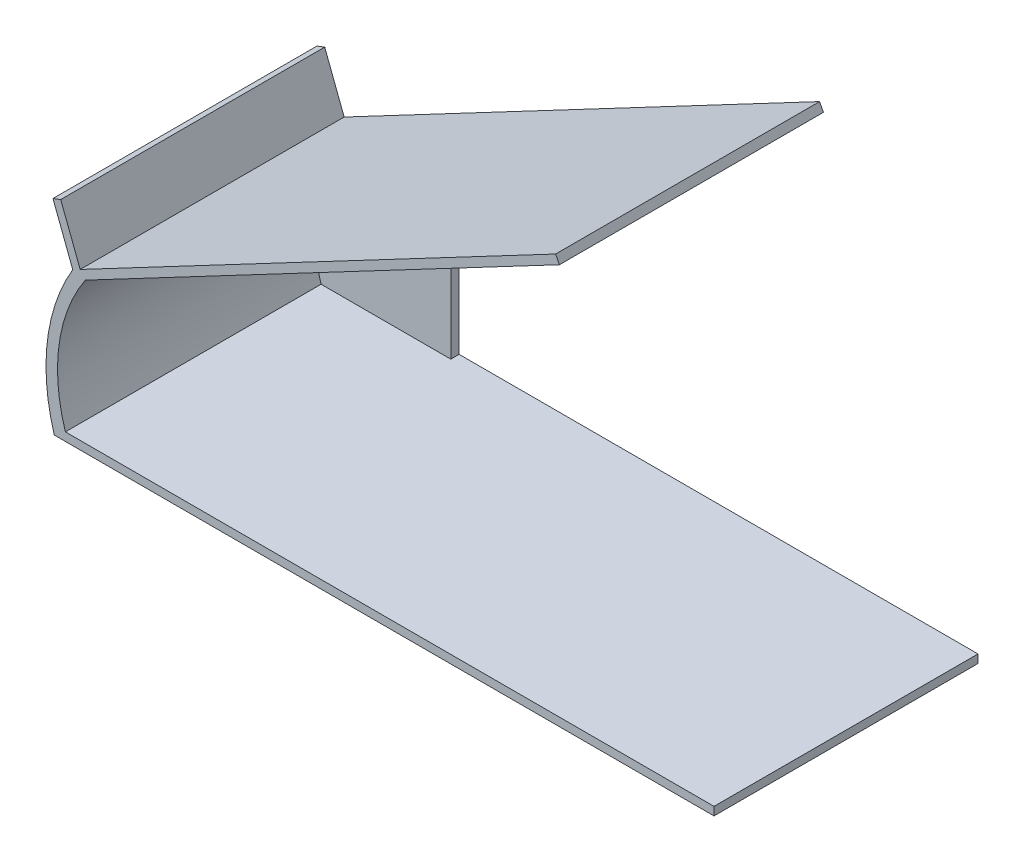
SolidWorks part; units mm, degrees
ref_plane "Front Plane" through (0, 0, 0) normal (0, 0, 1) x (1, 0, 0)
ref_plane "Top Plane" through (0, 0, 0) normal (0, 1, 0) x (1, 0, 0)
ref_plane "Right Plane" through (0, 0, 0) normal (1, 0, 0) x (0, 0, -1)
sketch "Sketch1" plane through (0, 0, 0) normal (0, 0, 1) x (1, 0, 0)
  line L0 (241, 0) -> (3, 0)
  line L1 (0, 0) -> (241, 0) construction
  line L2 (0, 0) -> (0, 147) construction
  line L3 (0, 147) -> (241, 147) construction
  line L4 (241, 0) -> (241, 147) construction
  line L5 (241, 0) -> (241, 3)
  line L6 (241, 3) -> (7, 3)
  line L7 (14.1823, 54) -> (185.251, 144.3472)
  line L8 (185.251, 144.3472) -> (183.85, 147)
  line L9 (183.85, 147) -> (9.6518, 55)
  arc A0 (9.6518, 55) -> (3, 0) centre (68.2435, 20.0115) ccw
  arc A1 (14.1823, 54) -> (7, 3) centre (63.1559, 21.0973) ccw
  dimension "D11" = 59
  dimension "D1" = 147
  dimension "D2" = 241
  dimension "D3" = 3
  dimension "D4" = 3
  dimension "D5" = 51
  dimension "D6" = 5
  dimension "D7" = 55
  dimension "D8" = 57.15
  dimension "D9" = 197
  dimension "D10" = 3
extrude "Boss-Extrude1" add sketch "Sketch1" along normal blind 95.25
ref_plane "Plane1" through (0, 0, 0) normal (0, 0, -1) x (-1, 0, 0)
sketch "Sketch2" plane through (0, 0, 0) normal (0, 0, -1) x (-1, 0, 0)
  line L0 (-53.8, 78.3162) -> (-53.8, 0)
  line L6 (-241, 3) -> (-241, 0)
  line L7 (-241, 0) -> (-3, 0)
  line L8 (-9.6518, 55) -> (-183.85, 147)
  line L9 (-183.85, 147) -> (-185.251, 144.3472)
  line L10 (-185.251, 144.3472) -> (-14.1823, 54)
  line L11 (-7, 3) -> (-241, 3)
  line L13 (-53.8, 0) -> (-3, 0)
  line L14 (-9.6518, 55) -> (-53.8, 78.3162)
  arc A2 (-3, 0) -> (-9.6518, 55) centre (-68.2435, 20.0115) ccw
  arc A3 (-7, 3) -> (-14.1823, 54) centre (-63.1559, 21.0973) ccw
  arc A4 (-3, 0) -> (-9.6518, 55) centre (-68.2435, 20.0115) ccw
  dimension "D2" = 50.8
  dimension "D1" = 0
extrude "Boss-Extrude2" add sketch "Sketch2" against normal blind 3
sketch "Sketch3" plane through (0, 0, 0) normal (0, 0, -1) x (-1, 0, 0)
  line L0 (-9.6518, 55) -> (-2.5072, 73.6803)
  line L1 (-2.5072, 73.6803) -> (-5.3092, 74.752)
  line L2 (-5.3092, 74.752) -> (-12.324, 56.4113)
  line L3 (-183.85, 147) -> (-9.6518, 55) construction
  line L4 (-12.324, 56.4113) -> (-9.6518, 55)
  point P3 (0, 0)
  point P8 (-4.3359, 82.094)
  point P9 (-3.9218, 83.0362)
  dimension "D1" = 3
  dimension "D2" = 20
  dimension "D3" = 96.91
extrude "Boss-Extrude3" add sketch "Sketch3" against normal up to surface (95.25 mm away) up to face at (109.1555, 50.9847, 95.25)
